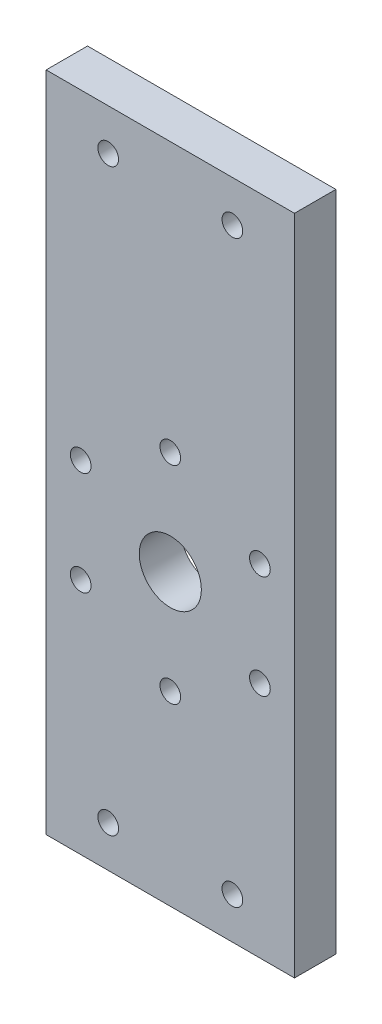
SolidWorks part; units mm, degrees
ref_plane "Front Plane" through (0, 0, 0) normal (0, 0, 1) x (1, 0, 0)
ref_plane "Top Plane" through (0, 0, 0) normal (0, 1, 0) x (1, 0, 0)
ref_plane "Right Plane" through (0, 0, 0) normal (1, 0, 0) x (0, 0, -1)
sketch "Sketch1" plane through (0, 0, 0) normal (0, 0, 1) x (1, 0, 0)
  line L1 (0, 0) -> (76.2, 0)
  line L2 (0, 0) -> (0, 203.2)
  line L3 (0, 203.2) -> (76.2, 203.2)
  line L4 (76.2, 0) -> (76.2, 203.2)
  dimension "D1" = 76.2
  dimension "D2" = 203.2
extrude "Boss-Extrude1" add sketch "Sketch1" along normal blind 12.7
sketch "Sketch2" plane through (0, 0, 0) normal (0, 0, -1) x (-1, 0, 0)
  line L1 (0, 203.2) -> (0, 0) construction
  line L2 (-76.2, 203.2) -> (0, 203.2) construction
  line L3 (0, 0) -> (-76.2, 0) construction
  circle A0 centre (-57.15, 190.5) radius 3.175
  circle A1 centre (-19.05, 190.5) radius 3.175
  circle A2 centre (-19.05, 12.7) radius 3.175
  circle A3 centre (-57.15, 12.7) radius 3.175
  dimension "D1" = 6.35
  dimension "D2" = 19.05
  dimension "D3" = 38.1
  dimension "D4" = 12.7
  dimension "D5" = 12.7
extrude "Cut-Extrude1" cut sketch "Sketch2" against normal up to surface (12.7 mm away) up to face at (38.1, 101.6, 12.7)
sketch "Sketch3" plane through (0, 0, 12.7) normal (0, 0, 1) x (1, 0, 0)
  line L1 (0, 0) -> (76.2, 0) construction
  line L2 (76.2, 0) -> (76.2, 203.2) construction
  circle A0 centre (38.1, 88.9) radius 9.525
  dimension "D1" = 88.9
  dimension "D3" = 19.05
  dimension "D2" = 38.1
extrude "Cut-Extrude2" cut sketch "Sketch3" against normal up to surface (12.7 mm away) up to face at (53.975, 12.7, 0)
sketch "Sketch4" plane through (0, 0, 12.7) normal (0, 0, 1) x (1, 0, 0)
  circle A0 centre (38.1, 88.9) radius 31.75 construction
  circle A1 centre (38.1, 120.65) radius 3.175
  circle A4 centre (65.5963, 104.775) radius 3.175
  circle A5 centre (65.5963, 73.025) radius 3.175
  circle A6 centre (38.1, 57.15) radius 3.175
  circle A7 centre (10.6037, 73.025) radius 3.175
  circle A8 centre (10.6037, 104.775) radius 3.175
  point P12 (38.1, 88.9)
  point P19 (38.1, 88.9)
  dimension "D1" = 63.5
  dimension "D2" = 6.35
  dimension "D3" = 6
extrude "Cut-Extrude3" cut sketch "Sketch4" against normal up to surface (12.7 mm away) up to face at (28.575, 88.9, 0)
